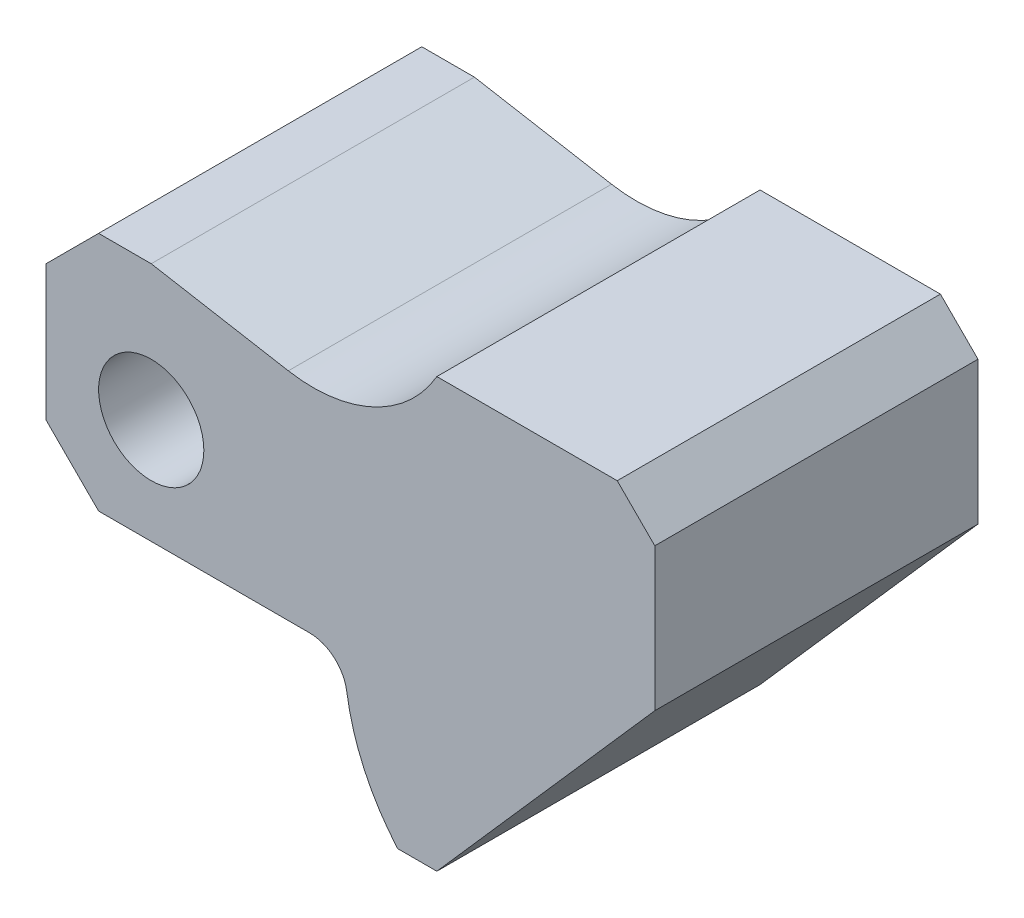
SolidWorks part; units mm, degrees
material "AISI 1020"
ref_plane "Front Plane" through (0, 0, 0) normal (0, 0, 1) x (1, 0, 0)
ref_plane "Top Plane" through (0, 0, 0) normal (0, 1, 0) x (1, 0, 0)
ref_plane "Right Plane" through (0, 0, 0) normal (1, 0, 0) x (0, 0, -1)
sketch "Esquisse1" plane through (0, 0, 0) normal (0, 0, 1) x (1, 0, 0)
  line L0 (0, 0) -> (5.2119, 0)
  line L1 (5.2119, 0) -> (34.2119, 33)
  line L2 (34.2119, 33) -> (34.2119, 52)
  line L3 (34.2119, 52) -> (29.2119, 57)
  line L4 (29.2119, 57) -> (5.2119, 57)
  line L11 (-14.545, 47.7833) -> (-32.7881, 51)
  line L12 (-32.7881, 51) -> (-39.7881, 51)
  line L13 (-39.7881, 51) -> (-46.7881, 44)
  line L14 (-46.7881, 44) -> (-46.7881, 26)
  line L15 (-46.7881, 26) -> (-39.7881, 19)
  line L16 (-39.7881, 19) -> (-11.7214, 19)
  arc A3 (5.2119, 57) -> (-14.545, 47.7833) centre (-11.2457, 66.4946) cw
  arc A4 (-11.7214, 19) -> (-6.7758, 14.7353) centre (-11.7214, 14) cw
  arc A5 (-6.7758, 14.7353) -> (0, 0) centre (21.9089, 19) ccw
  point P18 (-30.8653, 15.3614)
  point P19 (-30.3969, 13.2534)
  point P20 (0, 37.8465)
  point P21 (-10.254, 49.5576)
  point P22 (0, 46.9811)
  point P23 (-41.6395, 51.6655)
  point P24 (-39.0631, 20.5142)
  point P25 (-35.0813, 52.134)
  point P26 (-8.6488, 54.0576)
  point P27 (-25.0098, 57.2868)
  point P28 (-39.2973, 30.8199)
  point P29 (0, 0)
  point P30 (0, 0)
  point P31 (0, 0)
  point P32 (2.606, 0)
  point P33 (-14.545, 47.7833)
  point P34 (-14.545, 47.7833)
  point P35 (-14.545, 47.7833)
  point P36 (-11.7214, 52)
  point P37 (-11.7214, 52)
  dimension "D8" = 19
  dimension "D17" = 5
  dimension "D18" = 29
  dimension "D1" = 57
  dimension "D2" = 5
  dimension "D3" = 45
  dimension "D4" = 29
  dimension "D5" = 24
  dimension "D6" = 29
  dimension "D7" = 81
  dimension "D9" = 10
  dimension "D10" = 7
  dimension "D11" = 45
  dimension "D12" = 14
  dimension "D14" = 7
  dimension "D15" = 45
  dimension "D16" = 19
  dimension "D19" = 19
  dimension "D13" = 32
extrude "Boss.-Extru.1" add sketch "Esquisse1" along normal mid plane 43
sketch "Esquisse2" plane through (0, 0, 21.5) normal (0, 0, 1) x (1, 0, 0)
  line L0 (-46.7881, 44) -> (-46.7881, 26) construction
  line L1 (-39.7881, 19) -> (-11.7214, 19) construction
  circle A0 centre (-32.7881, 33) radius 7
  dimension "D1" = 14
  dimension "D2" = 14
  dimension "D3" = 14
extrude "Enlèv. mat.-Extru.1" cut sketch "Esquisse2" against normal through all
equation "\"A\" = 81"
equation "\"B\" = 57"
equation "\"C\"= 43"
equation "\"D1@Esquisse1\"=\"B\""
equation "\"D7@Esquisse1\"=\"A\""
equation "\"D1@Boss.-Extru.1\"=\"C\""
